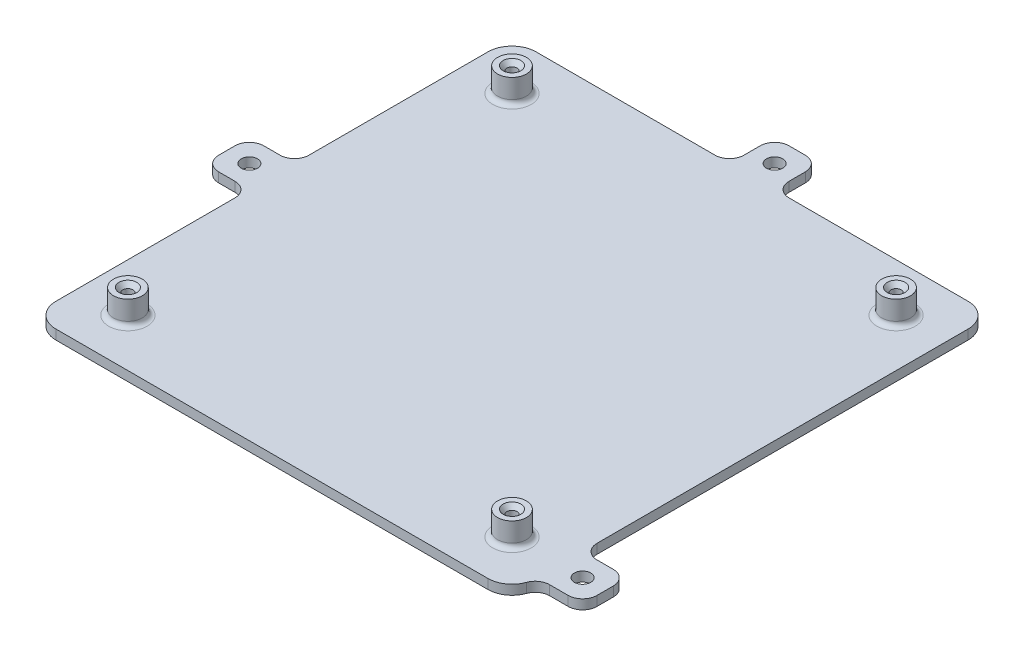
SolidWorks part; units mm, degrees
ref_plane "Ebene vorne" through (0, 0, 0) normal (0, 0, 1) x (1, 0, 0)
ref_plane "Ebene oben" through (0, 0, 0) normal (0, 1, 0) x (1, 0, 0)
ref_plane "Ebene rechts" through (0, 0, 0) normal (1, 0, 0) x (0, 0, -1)
sketch "Skizze1" plane through (0, 0, 0) normal (0, 1, 0) x (1, 0, 0)
  line L1 (0, 0) -> (80, 0) construction
  line L2 (0, 0) -> (0, -80) construction
  line L3 (0, -80) -> (80, -80) construction
  line L4 (80, 0) -> (80, -80) construction
  line L5 (0, 0) -> (80, -80) construction
  line L6 (0, -80) -> (80, 0) construction
  line L7 (-10, 10) -> (90, 10)
  line L8 (-10, 10) -> (-10, -90)
  line L9 (-10, -90) -> (90, -90)
  line L10 (90, 10) -> (90, -90)
  line L11 (-10, 10) -> (90, -90) construction
  line L12 (-10, -90) -> (90, 10) construction
  circle A0 centre (0, 0) radius 1.05
  circle A1 centre (0, -80) radius 1.05
  circle A2 centre (80, 0) radius 1.05
  circle A3 centre (80, -80) radius 1.05
  point P4 (40, -40)
  point P14 (40, -40)
  dimension "D3" = 2.1
  dimension "D1" = 80
  dimension "D2" = 80
  dimension "D4" = 10
extrude "Aufsatz-Linear austragen1" add sketch "Skizze1" along normal blind 2
sketch "Skizze2" plane through (0, 2, 0) normal (0, 1, 0) x (1, 0, 0)
  circle A0 centre (0, 0) radius 3
  circle A1 centre (80, 0) radius 3
  circle A2 centre (0, -80) radius 3
  circle A3 centre (80, -80) radius 3
  circle A4 centre (80, 0) radius 1.05 construction
  circle A5 centre (80, -80) radius 1.05 construction
  circle A6 centre (0, -80) radius 1.05 construction
  circle A7 centre (0, 0) radius 1.05 construction
  circle A8 centre (80, 0) radius 1.05
  circle A9 centre (80, -80) radius 1.05
  circle A10 centre (0, -80) radius 1.05
  circle A11 centre (0, 0) radius 1.05
  dimension "D1" = 6
extrude "Aufsatz-Linear austragen2" add sketch "Skizze2" along normal blind 5
fillet "Verrundung1" radius 1 4 edges at (80, 2, 83) (0, 2, 83) (80, 2, 3) (0, 2, 3)
chamfer "Fase1" distance 0.8 angle 50 5 edges at (80, 7, 81.05) (80, 0, 81.05) (80, 7, 1.05) (0, 7, 81.05) (0, 7, 1.05)
fillet "Verrundung2" radius 5 4 edges at (90, 1, 90) (-10, 1, 90) (90, 1, -10) (-10, 1, -10)
sketch "Skizze3" plane through (0, 2, 0) normal (0, 1, 0) x (1, 0, 0)
  line L0 (-10, -40) -> (90, -40) construction
  line L1 (-10, 5) -> (-10, -85) construction
  line L2 (90, -85) -> (90, 5) construction
  line L3 (-10, -40) -> (-19.4, -40) construction
  line L4 (-10, -35.3) -> (-19.4, -35.3)
  line L5 (-10, -35.3) -> (-10, -44.7)
  line L6 (-10, -44.7) -> (-19.4, -44.7)
  line L7 (-19.4, -35.3) -> (-19.4, -44.7)
  line L8 (-10, -35.3) -> (-19.4, -44.7) construction
  line L9 (-10, -44.7) -> (-19.4, -35.3) construction
  line L10 (90, -75.3) -> (99.4, -75.3)
  line L11 (90, -75.3) -> (90, -84.7)
  line L12 (90, -84.7) -> (99.4, -84.7)
  line L13 (99.4, -75.3) -> (99.4, -84.7)
  line L14 (90, -75.3) -> (99.4, -84.7) construction
  line L15 (90, -84.7) -> (99.4, -75.3) construction
  line L16 (-5, -90) -> (85, -90) construction
  circle A0 centre (-14.7, -40) radius 1.7
  circle A1 centre (94.7, -80) radius 1.7
  circle A2 centre (94.7, -80) radius 4.7 construction
  circle A3 centre (-14.7, -40) radius 4.7 construction
  point P10 (-14.7, -40)
  point P15 (94.7, -80)
  dimension "D2" = 3.4
  dimension "D3" = 3.4
  dimension "D4" = 3
  dimension "D1" = 3
  dimension "D5" = 10
extrude "Aufsatz-Linear austragen3" add sketch "Skizze3" against normal up to surface (2 mm away) up to face at (80, 0, 82.0034)
fillet "Verrundung3" radius 3 8 edges at (90, 1, 84.7) (99.4, 1, 84.7) (99.4, 1, 75.3) (90, 1, 75.3) (-10, 1, 35.3) (-10, 1, 44.7) (-19.4, 1, 44.7) (-19.4, 1, 35.3)
sketch "Skizze4" plane through (0, 2, 0) normal (0, 1, 0) x (1, 0, 0)
  line L0 (40, 10) -> (40, -90) construction
  line L1 (85, 10) -> (-5, 10) construction
  line L2 (-5, -90) -> (85, -90) construction
  line L3 (40, 10) -> (40, 32.3177) construction
  line L6 (35.3, 19.4) -> (44.7, 19.4)
  line L7 (35.3, 19.4) -> (35.3, 10)
  line L8 (35.3, 10) -> (44.7, 10)
  line L9 (44.7, 19.4) -> (44.7, 10)
  line L10 (35.3, 19.4) -> (44.7, 10) construction
  line L11 (35.3, 10) -> (44.7, 19.4) construction
  circle A0 centre (40, 14.7) radius 1.7
  circle A2 centre (40, 14.7) radius 4.7 construction
  point P12 (40, 14.7)
  dimension "D1" = 3.4
  dimension "D2" = 3
extrude "Aufsatz-Linear austragen4" add sketch "Skizze4" against normal up to surface (2 mm away) up to face at (80, 0, 82.0034)
fillet "Verrundung4" radius 3 4 edges at (35.3, 1, -10) (44.7, 1, -10) (44.7, 1, -19.4) (35.3, 1, -19.4)
equation "\"D3@Skizze3\"=\"D2@Skizze3\""
